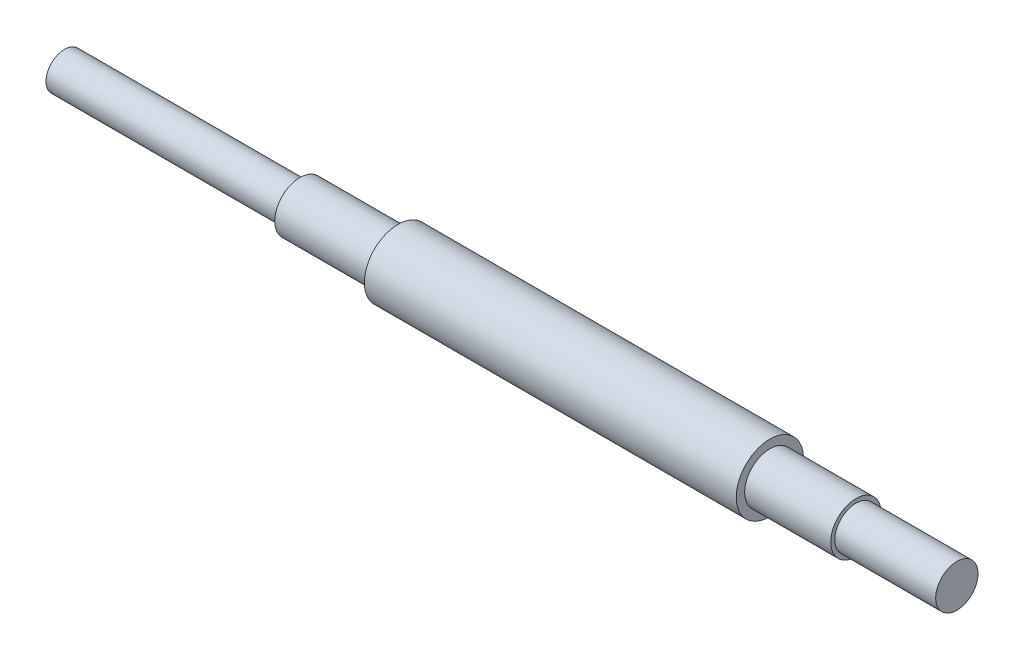
SolidWorks part; units mm, degrees
material "Plain Carbon Steel"
ref_plane "Front Plane" through (0, 0, 0) normal (0, 0, 1) x (1, 0, 0)
ref_plane "Top Plane" through (0, 0, 0) normal (0, 1, 0) x (1, 0, 0)
ref_plane "Right Plane" through (0, 0, 0) normal (1, 0, 0) x (0, 0, -1)
sketch "Sketch1" plane through (0, 0, 0) normal (0, 1, 0) x (1, 0, 0)
  line L0 (-78.6306, 0) -> (89.8554, 0) construction
  line L1 (-78.6306, 0) -> (-78.6306, 3.5)
  line L2 (-78.6306, 3.5) -> (-34.1806, 3.5)
  line L3 (-34.1806, 3.5) -> (-34.1806, 4.7625)
  line L4 (-34.1806, 4.7625) -> (-15.6689, 4.7625)
  line L5 (-15.6689, 4.7625) -> (-15.6689, 6.35)
  line L6 (-15.6689, 6.35) -> (54.5494, 6.35)
  line L7 (54.5494, 6.35) -> (54.5494, 4.7625)
  line L8 (54.5494, 4.7625) -> (70.8054, 4.7625)
  line L9 (70.8054, 4.7625) -> (70.8054, 3.9992)
  line L10 (70.8054, 3.9992) -> (89.8554, 3.9992)
  line L11 (89.8554, 3.9992) -> (89.8554, 0)
  line L12 (-78.6306, 0) -> (89.8554, 0)
  line L13 (-97.9506, 0) -> (194.5593, 0) construction
  dimension "D1" = 7
  dimension "D2" = 9.525
  dimension "D3" = 9.525
  dimension "D4" = 7.9985
  dimension "D5" = 44.45
  dimension "D6" = 18.5117
  dimension "D7" = 16.256
  dimension "D8" = 19.05
  dimension "D9" = 70.2182
  dimension "D10" = 6.35
revolve "Revolve1" add sketch "Sketch1" angle 360 about L13
